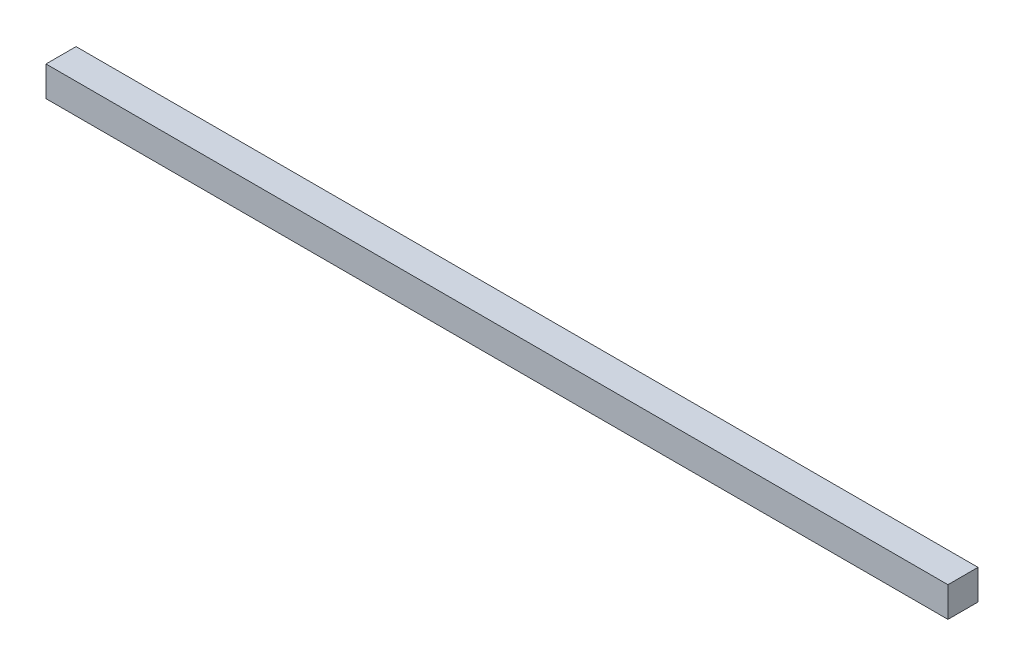
SolidWorks part; units mm, degrees
material "Pine"
ref_plane "Front Plane" through (0, 0, 0) normal (0, 0, 1) x (1, 0, 0)
ref_plane "Top Plane" through (0, 0, 0) normal (0, 1, 0) x (1, 0, 0)
ref_plane "Right Plane" through (0, 0, 0) normal (1, 0, 0) x (0, 0, -1)
sketch "Sketch1" plane through (0, 0, 0) normal (0, 0, 1) x (1, 0, 0)
  line L1 (-571.5, 19.05) -> (571.5, 19.05)
  line L2 (-571.5, 19.05) -> (-571.5, -19.05)
  line L3 (-571.5, -19.05) -> (571.5, -19.05)
  line L4 (571.5, 19.05) -> (571.5, -19.05)
  point P4 (0, 19.05)
  point P6 (571.5, 0)
  dimension "D1" = 1143
  dimension "D2" = 38.1
extrude "Boss-Extrude1" add sketch "Sketch1" along normal blind 38.1
